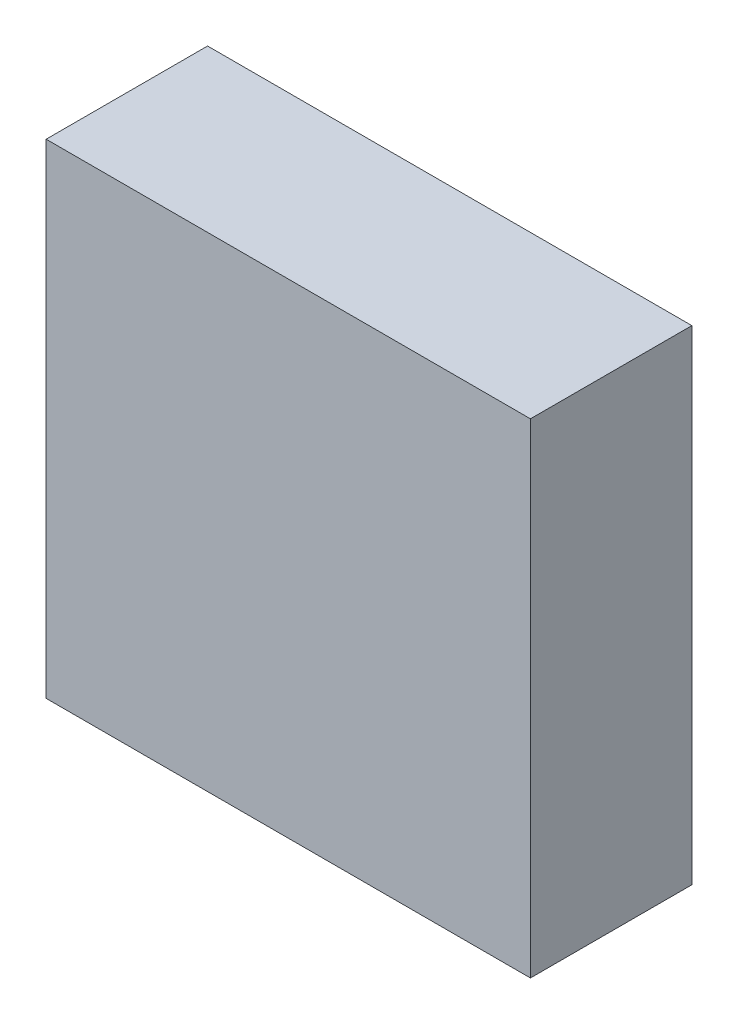
SolidWorks part; units mm, degrees
ref_plane "前视基准面" through (0, 0, 0) normal (0, 0, 1) x (1, 0, 0)
ref_plane "上视基准面" through (0, 0, 0) normal (0, 1, 0) x (1, 0, 0)
ref_plane "右视基准面" through (0, 0, 0) normal (1, 0, 0) x (0, 0, -1)
sketch "草图1" plane through (0, 0, 0) normal (1, 0, 0) x (0, 0, -1)
  line L1 (5, 15) -> (-5, 15)
  line L2 (5, 15) -> (5, -15)
  line L3 (5, -15) -> (-5, -15)
  line L4 (-5, 15) -> (-5, -15)
  line L5 (5, 15) -> (-5, -15) construction
  line L6 (5, -15) -> (-5, 15) construction
  point P0 (0, 0)
  point P6 (0, 0)
  point P7 (0, 0)
  point P8 (0, 0)
  point P9 (0, 0)
extrude "凸台-拉伸1" add sketch "草图1" along normal blind 30
sketch "草图2" plane through (0, 0, -5) normal (0, 0, -1) x (-1, 0, 0)
  circle A0 centre (-15, -10) radius 3
extrude "凸台-拉伸2" add sketch "草图2" along normal blind 10
